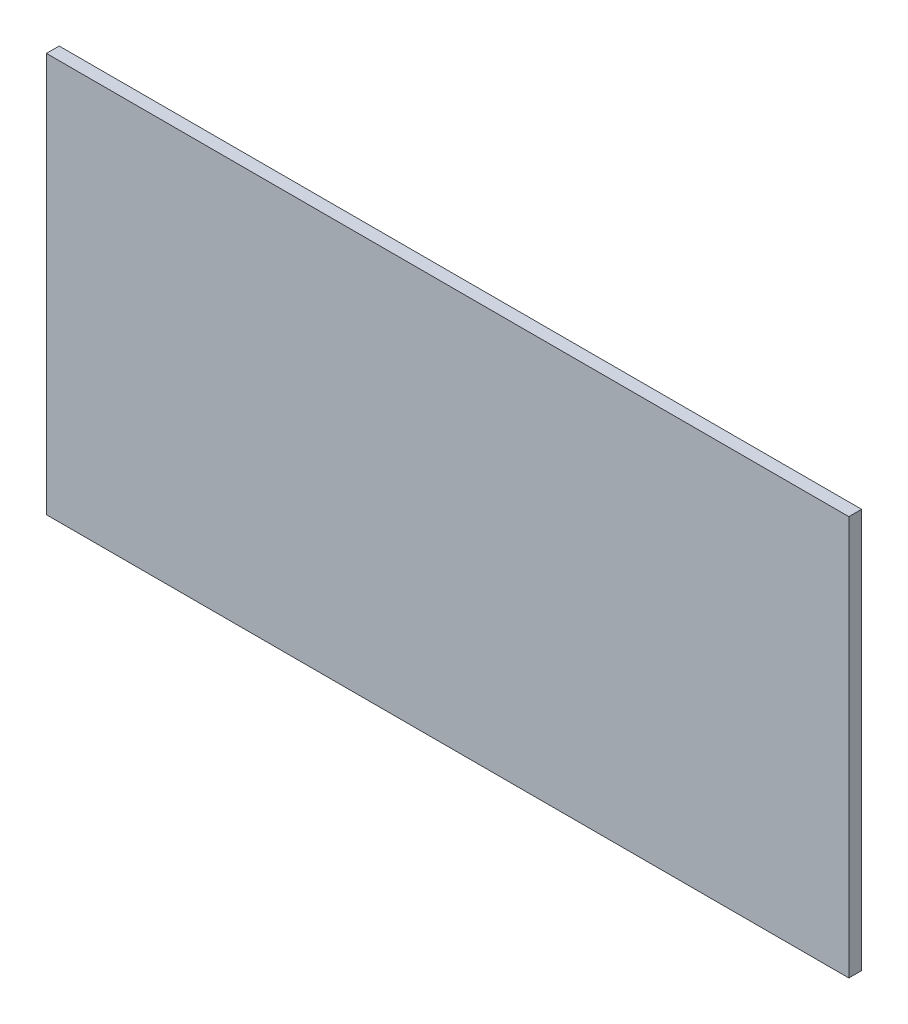
SolidWorks part; units mm, degrees
material "Pine"
ref_plane "Front Plane" through (0, 0, 0) normal (0, 0, 1) x (1, 0, 0)
ref_plane "Top Plane" through (0, 0, 0) normal (0, 1, 0) x (1, 0, 0)
ref_plane "Right Plane" through (0, 0, 0) normal (1, 0, 0) x (0, 0, -1)
sketch "Sketch1" plane through (0, 0, 0) normal (0, 0, 1) x (1, 0, 0)
  line L1 (-573.8813, 285.75) -> (573.8813, 285.75)
  line L2 (-573.8813, 285.75) -> (-573.8813, -285.75)
  line L3 (-573.8813, -285.75) -> (573.8813, -285.75)
  line L4 (573.8813, 285.75) -> (573.8813, -285.75)
  line L5 (0, -285.75) -> (0, 285.75) construction
  line L6 (-573.8813, 0) -> (573.8813, 0) construction
  point P0 (0, 0)
  dimension "D1" = 1147.7625
  dimension "D2" = 571.5
extrude "Boss-Extrude1" add sketch "Sketch1" along normal blind 18.2562
